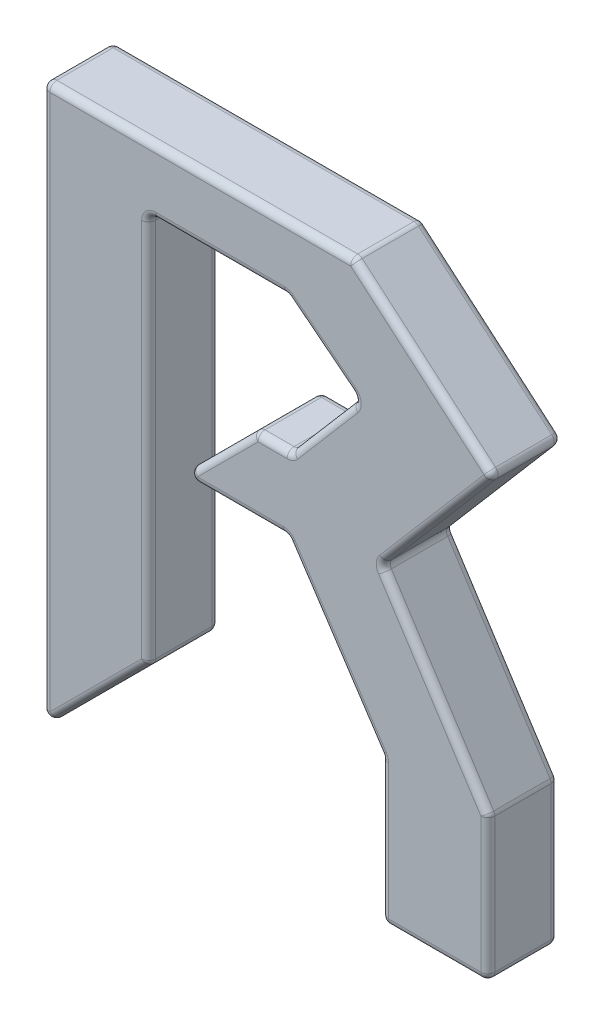
SolidWorks part; units mm, degrees
ref_plane "Front Plane" through (0, 0, 0) normal (0, 0, 1) x (1, 0, 0)
ref_plane "Top Plane" through (0, 0, 0) normal (0, 1, 0) x (1, 0, 0)
ref_plane "Right Plane" through (0, 0, 0) normal (1, 0, 0) x (0, 0, -1)
sketch "Sketch3" plane through (0, 0, 0) normal (0, 0, 1) x (1, 0, 0)
  line L0 (0, 0) -> (0, 69.7471)
  line L2 (15.0677, 15.5776) -> (15.0677, 60.5226)
  line L4 (0, 69.7471) -> (44.1811, 69.7471)
  line L5 (44.1811, 69.7471) -> (64.1829, 52.6262)
  line L6 (63.3304, 10.5365) -> (63.3304, -0.0755) construction
  line L7 (64.1829, 52.6262) -> (48.2084, 33.9637)
  line L9 (63.3304, 0) -> (63.3304, -10)
  line L10 (48.2084, 33.9637) -> (63.3304, 10.5365)
  line L11 (63.3304, 10.5365) -> (63.3304, -0.0755)
  line L12 (63.3304, -10) -> (48.2084, -10)
  line L13 (48.2084, -10) -> (48.2084, 0)
  line L14 (15.0677, 60.5226) -> (34.7461, 60.5226)
  line L15 (0, 0) -> (0, -10)
  line L16 (34.7461, 60.5226) -> (44.7541, 52.6262)
  line L17 (0, -10) -> (15.0677, 5.0677)
  line L18 (44.7541, 52.6262) -> (35.2201, 41.4879)
  line L19 (30.2201, 41.4879) -> (35.2201, 41.4879)
  line L20 (15.0677, 5.0677) -> (15.0677, 15.5776)
  line L21 (30.2201, 41.4879) -> (19.6135, 30.8813)
  line L23 (19.6135, 30.8813) -> (34.7461, 30.8813)
  line L24 (34.7461, 30.8813) -> (48.2084, 10.5365)
  line L25 (48.2084, 10.5365) -> (48.2084, 0)
extrude "Boss-Extrude1" add sketch "Sketch3" along normal blind 10
fillet "Fillet3" radius 1 51 edges at (48.2084, 10.5365, 5) (48.2084, -10, 5) (63.3304, -10, 5) (63.3304, 10.5365, 5) (48.2084, 33.9637, 5) (64.1829, 52.6262, 5) (44.1811, 69.7471, 5) (0, 69.7471, 5) (0, -10, 5) (15.0677, 5.0677, 5) (15.0677, 60.5226, 5) (34.7461, 60.5226, 5) (44.7541, 52.6262, 5) (35.2201, 41.4879, 5) (30.2201, 41.4879, 5) (19.6135, 30.8813, 5) (34.7461, 30.8813, 5) (27.1798, 30.8813, 10) (24.9168, 36.1846, 10) (32.7201, 41.4879, 10) (39.9871, 47.057, 10) (39.7501, 56.5744, 10) (24.9069, 60.5226, 10) (15.0677, 32.7952, 10) (7.5339, -2.4661, 10) (0, 29.8735, 10) (22.0905, 69.7471, 10) (54.182, 61.1866, 10) (56.1956, 43.295, 10) (55.7694, 22.2501, 10) (63.3304, 0.2683, 10) (55.7694, -10, 10) (48.2084, 0.2683, 10) (41.4773, 20.7089, 10) (27.1798, 30.8813, 0) (24.9168, 36.1846, 0) (32.7201, 41.4879, 0) (39.9871, 47.057, 0) (39.7501, 56.5744, 0) (24.9069, 60.5226, 0) (15.0677, 32.7952, 0) (7.5339, -2.4661, 0) (0, 29.8735, 0) (22.0905, 69.7471, 0) (54.182, 61.1866, 0) (56.1956, 43.295, 0) (55.7694, 22.2501, 0) (63.3304, 0.2683, 0) (55.7694, -10, 0) (48.2084, 0.2683, 0) (41.4773, 20.7089, 0)
